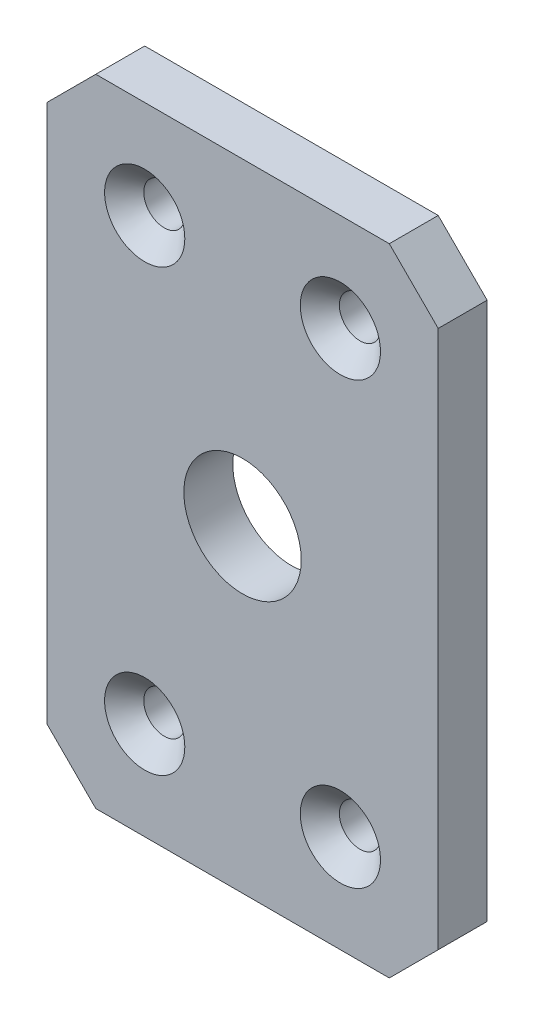
SolidWorks part; units mm, degrees
ref_plane "前视基准面" through (0, 0, 0) normal (0, 0, 1) x (1, 0, 0)
ref_plane "上视基准面" through (0, 0, 0) normal (0, 1, 0) x (1, 0, 0)
ref_plane "右视基准面" through (0, 0, 0) normal (1, 0, 0) x (0, 0, -1)
sketch "草图1" plane through (0, 0, 0) normal (0, 0, 1) x (1, 0, 0)
  line L1 (20, -32.5) -> (-20, -32.5)
  line L2 (20, -32.5) -> (20, 32.5)
  line L3 (20, 32.5) -> (-20, 32.5)
  line L4 (-20, -32.5) -> (-20, 32.5)
  line L5 (20, -32.5) -> (-20, 32.5) construction
  line L6 (20, 32.5) -> (-20, -32.5) construction
  circle A0 centre (0, 0) radius 6
  dimension "D1" = 12
  dimension "D2" = 65
  dimension "D3" = 40
extrude "凸台-拉伸1" add sketch "草图1" along normal mid plane 5
sketch "草图2" plane through (0, 0, -2.5) normal (0, 0, -1) x (-1, 0, 0)
  line L0 (-20, 32.5) -> (20, 32.5) construction
  line L1 (10, -22.5) -> (-10, -22.5) construction
  line L2 (10, -22.5) -> (10, 22.5) construction
  line L3 (10, 22.5) -> (-10, 22.5) construction
  line L4 (-10, -22.5) -> (-10, 22.5) construction
  line L5 (10, -22.5) -> (-10, 22.5) construction
  line L6 (10, 22.5) -> (-10, -22.5) construction
  line L7 (-20, -32.5) -> (-20, 32.5) construction
  circle A0 centre (-10, 22.5) radius 2.1
  circle A1 centre (10, 22.5) radius 2.1
  circle A2 centre (10, -22.5) radius 2.1
  circle A3 centre (-10, -22.5) radius 2.1
  point P0 (0, 0)
  dimension "D1" = 10
  dimension "D3" = 4.2
  dimension "D2" = 10
extrude "切除-拉伸1" cut sketch "草图2" against normal through all both and the other way through all
chamfer "倒角1" distance 2 angle 45 4 edges at (7.9, -22.5, 2.5) (-12.1, -22.5, 2.5) (7.9, 22.5, 2.5) (-12.1, 22.5, 2.5)
chamfer "倒角2" distance 5 angle 45 4 edges at (20, 32.5, 0) (20, -32.5, 0) (-20, -32.5, 0) (-20, 32.5, 0)
